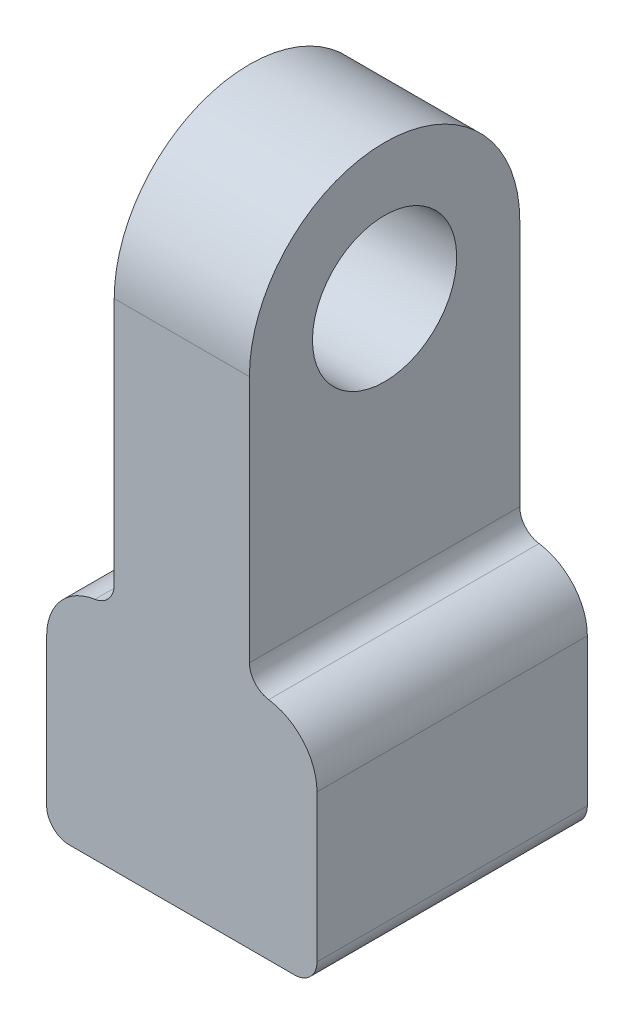
SolidWorks part; units mm, degrees
ref_plane "正面" through (0, 0, 0) normal (0, 0, 1) x (1, 0, 0)
ref_plane "平面" through (0, 0, 0) normal (0, 1, 0) x (1, 0, 0)
ref_plane "右側面" through (0, 0, 0) normal (1, 0, 0) x (0, 0, -1)
sketch "ｽｹｯﾁ1" plane through (0, 0, 0) normal (0, 0, 1) x (1, 0, 0)
  line L0 (1.5, 14) -> (-1.5, 14)
  line L1 (-1.5, 14) -> (-1.5, 5)
  line L2 (-1.5, 5) -> (-3, 5)
  line L3 (-3, 5) -> (-3, 0)
  line L4 (-3, 0) -> (3, 0)
  line L5 (0, 0) -> (0, 14) construction
  line L6 (-3, 2.5) -> (0, 2.5) construction
  line L7 (1.5, 5) -> (3, 5)
  line L8 (3, 5) -> (3, 0)
  line L9 (1.5, 14) -> (1.5, 5)
  dimension "D1" = 1.5
  dimension "D2" = 9
  dimension "D3" = 3
  dimension "D4" = 5
extrude "ﾎﾞｽ - 押し出し1" add sketch "ｽｹｯﾁ1" along normal mid plane 6
fillet "ﾌｨﾚｯﾄ1" radius 0.5 4 edges at (1.5, 5, 0) (-1.5, 5, 0) (3, 0, 0) (-3, 0, 0)
fillet "ﾌｨﾚｯﾄ2" radius 1.25 2 edges at (3, 5, 0) (-3, 5, 0)
sketch "ｽｹｯﾁ3" plane through (-1.5, 0, 0) normal (-1, 0, 0) x (0, 0, 1)
  line L0 (-3, 11) -> (3, 11) construction
  line L4 (-3, 14) -> (-3, 5.5) construction
  line L5 (3, 14) -> (3, 5.5) construction
  circle A0 centre (0, 11) radius 1.6
  point P2 (0, 0)
  point P4 (0, 0)
  point P8 (0, 0)
  point P10 (0, 0)
  dimension "D1" = 3.2
  dimension "D2" = 11
extrude "ｶｯﾄ - 押し出し2" cut sketch "ｽｹｯﾁ3" against normal through all
sketch "ｽｹｯﾁ4" plane through (0, 0, 0) normal (0, -1, 0) x (1, 0, 0)
  circle A0 centre (0, 0) radius 2.05
  dimension "D1" = 4.1
extrude "ｶｯﾄ - 押し出し4" cut sketch "ｽｹｯﾁ4" against normal blind 4
sketch "ｽｹｯﾁ5" plane through (-1.5, 0, 0) normal (-1, 0, 0) x (0, 0, 1)
  line L0 (3, 14) -> (-3, 14) construction
  line L1 (-3, 11) -> (-3, 14)
  line L2 (-3, 14) -> (3, 14)
  line L3 (3, 14) -> (3, 11)
  arc A0 (3, 11) -> (-3, 11) centre (0, 11) ccw
  line M3 (-3, 14) -> (-3, 5.5)
  line M5 (3, 5.5) -> (3, 14)
  line M6 (3, 14) -> (-3, 14)
extrude "ｶｯﾄ - 押し出し5" cut sketch "ｽｹｯﾁ5" against normal through all contours A0 L2 M3 | A0 M5 M6
